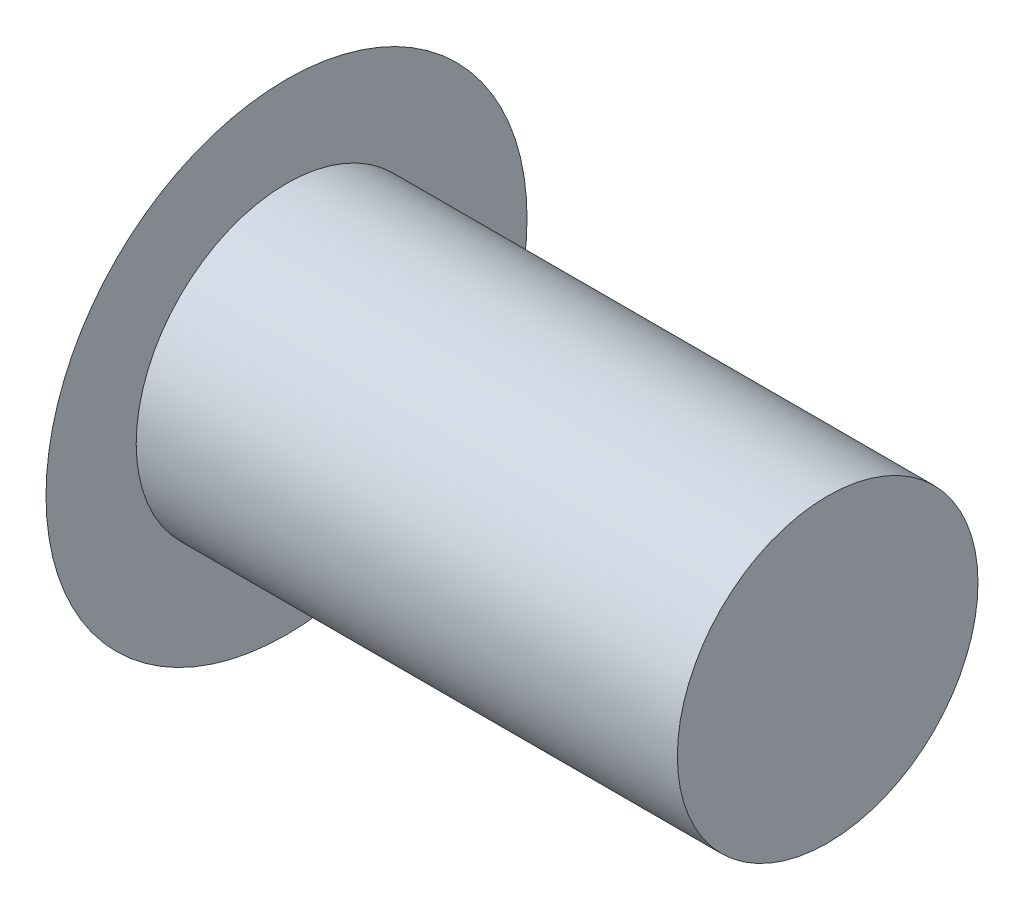
SolidWorks part; units mm, degrees
ref_plane "Front Plane" through (0, 0, 0) normal (0, 0, 1) x (1, 0, 0)
ref_plane "Top Plane" through (0, 0, 0) normal (0, 1, 0) x (1, 0, 0)
ref_plane "Right Plane" through (0, 0, 0) normal (1, 0, 0) x (0, 0, -1)
sketch "Sketch1" plane through (0, 0, 0) normal (1, 0, 0) x (0, 0, -1)
  circle A0 centre (0, 0) radius 5
  dimension "D1" = 10
extrude "Boss-Extrude1" add sketch "Sketch1" along normal blind 18
sketch "Sketch2" plane through (0, 0, 0) normal (-1, 0, 0) x (0, 0, 1)
  circle A0 centre (0, 0) radius 8
  circle A1 centre (0, 0) radius 5 construction
  dimension "D1" = 3
extrude "Boss-Extrude2" add sketch "Sketch2" along normal blind 3 draft 60
sketch "Sketch4" plane through (-3, 0, 0) normal (-1, 0, 0) x (0, 0, 1)
  line L1 (2.3408, 0) -> (1.1704, 2.0272)
  line L2 (1.1704, 2.0272) -> (-1.1704, 2.0272)
  line L3 (-1.1704, 2.0272) -> (-2.3408, 0)
  line L4 (-2.3408, 0) -> (-1.1704, -2.0272)
  line L5 (-1.1704, -2.0272) -> (1.1704, -2.0272)
  line L6 (1.1704, -2.0272) -> (2.3408, 0)
  circle A0 centre (0, 0) radius 2.0272 construction
extrude "Cut-Extrude1" cut sketch "Sketch4" against normal blind 1
fillet "Fillet1" radius 0.5 6 edges at (-2, -2.0272, 0) (-2, -1.0136, -1.7556) (-2, 1.0136, -1.7556) (-2, 2.0272, 0) (-2, 1.0136, 1.7556) (-2, -1.0136, 1.7556)
